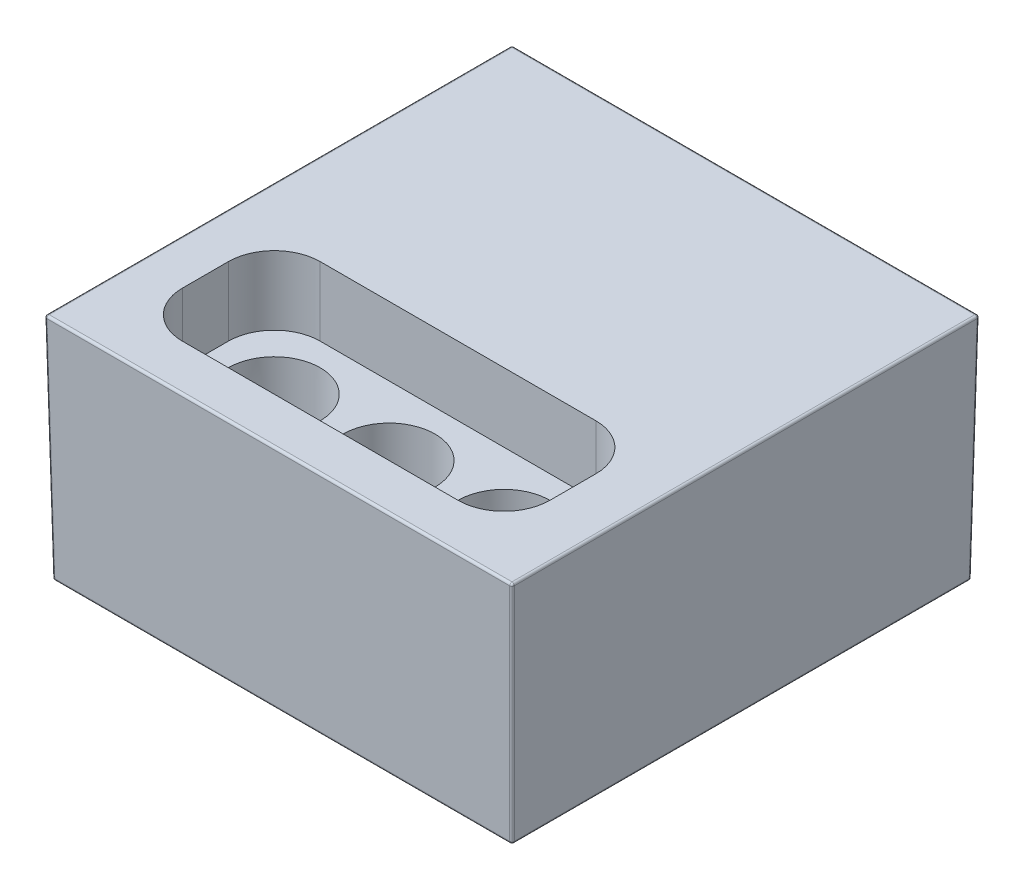
SolidWorks part; units mm, degrees
material "Steel, Hot Worked, AISI 1095"
ref_plane "Front Plane" through (0, 0, 0) normal (0, 0, 1) x (1, 0, 0)
ref_plane "Top Plane" through (0, 0, 0) normal (0, 1, 0) x (1, 0, 0)
ref_plane "Right Plane" through (0, 0, 0) normal (1, 0, 0) x (0, 0, -1)
sketch "Sketch1" plane through (0, 0, 0) normal (0, 1, 0) x (1, 0, 0)
  line L1 (0, 0) -> (100, 0)
  line L2 (0, 0) -> (0, 100)
  line L3 (0, 100) -> (100, 100)
  line L4 (100, 0) -> (100, 100)
  dimension "D1" = 100
  dimension "D2" = 100
extrude "Boss-Extrude1" add sketch "Sketch1" along normal blind 50 draft 1 draft outward yes
sketch "Sketch3" plane through (0, 50, 0) normal (0, 1, 0) x (1, 0, 0)
  line L0 (-0.8728, 100.8728) -> (-0.8728, -0.8728) construction
  line L1 (9.1272, 9.1272) -> (89.1272, 9.1272)
  line L2 (9.1272, 9.1272) -> (9.1272, 39.1272)
  line L3 (9.1272, 39.1272) -> (89.1272, 39.1272)
  line L4 (89.1272, 9.1272) -> (89.1272, 39.1272)
  line L5 (-0.8728, -0.8728) -> (100.8728, -0.8728) construction
  dimension "D1" = 10
  dimension "D2" = 80
  dimension "D3" = 10
  dimension "D4" = 30
extrude "Cut-Extrude2" cut sketch "Sketch3" against normal blind 15
fillet "Fillet1" radius 10 4 edges at (89.1272, 42.5, -9.1272) (89.1272, 42.5, -39.1272) (9.1272, 42.5, -39.1272) (9.1272, 42.5, -9.1272)
sketch "Sketch4" plane through (0, 35, 0) normal (0, 1, 0) x (1, 0, 0)
  line L0 (-0.8728, 100.8728) -> (-0.8728, -0.8728) construction
  line L1 (-0.8728, -0.8728) -> (100.8728, -0.8728) construction
  circle A0 centre (24.1272, 24.1272) radius 10
  circle A2 centre (74.1272, 24.1272) radius 10
  dimension "D1" = 20
  dimension "D2" = 50
  dimension "D4" = 25
  dimension "D5" = 25
extrude "Cut-Extrude3" cut sketch "Sketch4" against normal blind 15 draft 0.5
sketch "Sketch5" plane through (0, 35, 0) normal (0, 1, 0) x (1, 0, 0)
  line L0 (-0.8728, -0.8728) -> (100.8728, -0.8728) construction
  circle A0 centre (49.1272, 24.1272) radius 10
  circle A2 centre (24.1272, 24.1272) radius 10 construction
  dimension "D1" = 20
  dimension "D2" = 25
  dimension "D3" = 25
extrude "Cut-Extrude4" cut sketch "Sketch5" against normal blind 30
fillet "Fillet2" radius 0.5 12 edges at (50, 0, 0) (100, 0, -50) (50, 0, -100) (0, 0, -50) (100.4364, 25, -100.4364) (100.8728, 50, -50) (50, 50, -100.8728) (-0.4364, 25, -100.4364) (100.4364, 25, 0.4364) (50, 50, 0.8728) (-0.8728, 50, -50) (-0.4364, 25, 0.4364)
